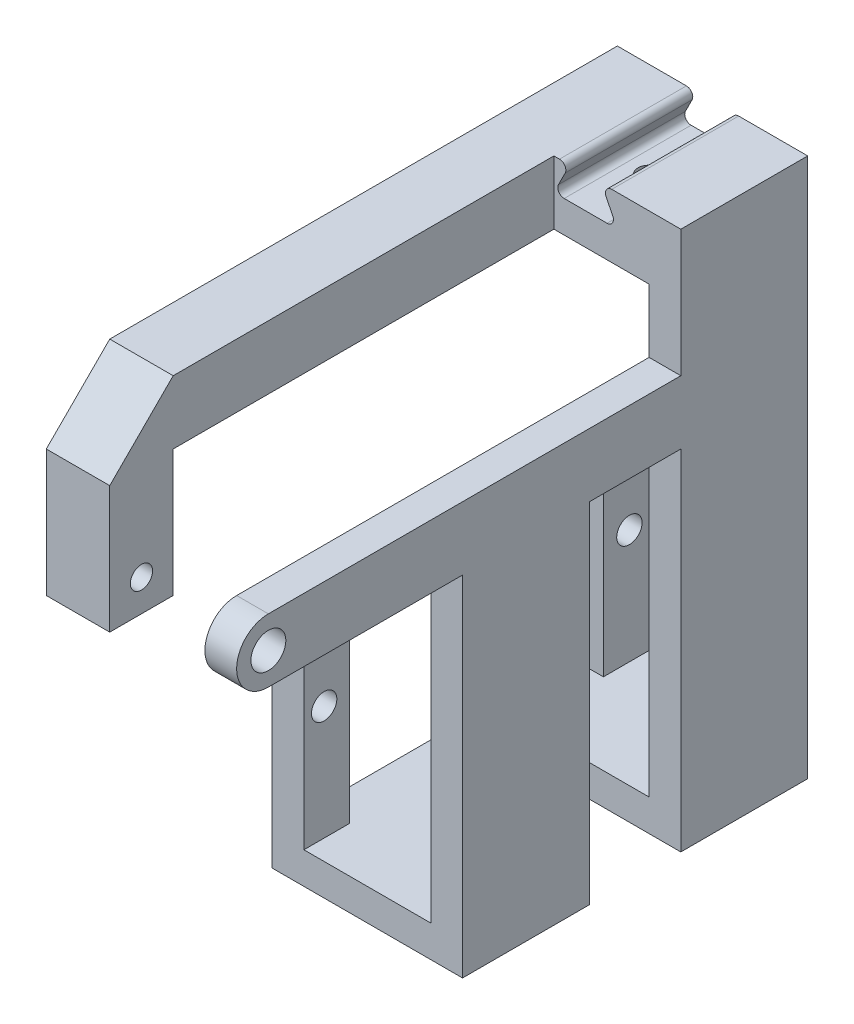
SolidWorks part; units mm, degrees
ref_plane "Plano frontal" through (0, 0, 0) normal (0, 0, 1) x (1, 0, 0)
ref_plane "Plano superior" through (0, 0, 0) normal (0, 1, 0) x (1, 0, 0)
ref_plane "Plano direito" through (0, 0, 0) normal (1, 0, 0) x (0, 0, -1)
sketch "Esboço1" plane through (0, 0, 0) normal (0, 0, 1) x (1, 0, 0)
  line L1 (-15, 45) -> (15, 45)
  line L2 (-15, 45) -> (-15, -45)
  line L3 (-15, -45) -> (15, -45)
  line L4 (15, 45) -> (15, 35)
  line L6 (-15, 35) -> (15, 35)
  line L7 (-10, 35) -> (-10, -45)
  line L8 (-10, -35) -> (15, -35)
  line L9 (10, -35) -> (10, -2)
  line L10 (10, -2) -> (15, -2)
  line L11 (15, -2) -> (15, -35)
  line L12 (15, -35) -> (15, -45)
  line L13 (-2.5, 45) -> (-5, 40)
  line L14 (-5, 40) -> (5, 40)
  line L15 (5, 40) -> (2.5, 45)
  point P1 (-15, 0)
  point P6 (0, 45)
  point P22 (0, 40)
  dimension "D1" = 30
  dimension "D2" = 90
  dimension "D4" = 10
  dimension "D5" = 5
  dimension "D6" = 10
  dimension "D7" = 5
  dimension "D8" = 33
  dimension "D9" = 20
  dimension "D10" = 5
  dimension "D11" = 10
  dimension "D12" = 5
extrude "Ressalto-extrusão1" add sketch "Esboço1" along normal blind 80 contours L15 L14 L13 L1 L2 L6 L4 | L7 L6 L2 L3 | L12 L8 L7 L3 | L11 L10 L9 L8
sketch "Esboço2" plane through (15, 0, 0) normal (1, 0, 0) x (0, 0, -1)
  line L5 (-80, -2) -> (0, -2) construction
  line L6 (-47.2, -2) -> (-7.2, -2)
  line L7 (-47.2, -2) -> (-47.2, -35)
  line L8 (-47.2, -35) -> (-7.2, -35)
  line L9 (-7.2, -2) -> (-7.2, -35)
  line L10 (-80, -45) -> (0, -45) construction
  line L11 (0, -2) -> (0, -45) construction
  line L13 (-80, -2) -> (-54.4, -2)
  line L14 (-80, -2) -> (-80, -35)
  line L15 (-80, -35) -> (-54.4, -35)
  line L16 (-54.4, -2) -> (-54.4, -35)
  dimension "D1" = 10
  dimension "D2" = 40
  dimension "D3" = 7.2
  dimension "D4" = 7.2
extrude "Corte-extrusão1" cut sketch "Esboço2" against normal blind 19
sketch "Esboço4" plane through (10, 0, 0) normal (-1, 0, 0) x (0, 0, 1)
  circle A0 centre (3.1042, -7.0008) radius 2
  circle A1 centre (3.1042, -17.0025) radius 2
  circle A2 centre (51.2105, -17.0025) radius 2
  circle A3 centre (51.2105, -7.0008) radius 2
extrude "Corte-extrusão3" cut sketch "Esboço4" against normal blind 12
sketch "Esboço5" plane through (15, 0, 0) normal (1, 0, 0) x (0, 0, -1)
  line L0 (-90, 35) -> (-80, 45)
  line L1 (-90, 35) -> (-80, 35)
  line L2 (-90, 35) -> (-90, 15)
  line L3 (-90, 15) -> (-80, 15)
  line L4 (-80, 35) -> (-80, 15)
  line L5 (-80, 45) -> (-80, 35)
  line M5 (-80, 45) -> (-80, 35)
  dimension "D1" = 10
  dimension "D2" = 20
extrude "Ressalto-extrusão2" add sketch "Esboço5" against normal blind 10 contours L4 L1 L2 L3 | L0 L1 M5
sketch "Esboço6" plane through (15, 0, 0) normal (1, 0, 0) x (0, 0, -1)
  line L2 (-80, 35) -> (-80, 15) construction
  line L3 (-90, 15) -> (-80, 15) construction
  circle A0 centre (-85, 20) radius 1.75
  dimension "D3" = 3.5
  dimension "D1" = 5
  dimension "D2" = 5
extrude "Corte-extrusão4" cut sketch "Esboço6" against normal blind 15
sketch "Esboço7" plane through (15, 0, 0) normal (1, 0, 0) x (0, 0, -1)
  line L1 (-81.75, 21.8764) -> (-85, 23.7528)
  line L2 (-85, 23.7528) -> (-88.25, 21.8764)
  line L3 (-88.25, 21.8764) -> (-88.25, 18.1236)
  line L4 (-88.25, 18.1236) -> (-85, 16.2472)
  line L5 (-85, 16.2472) -> (-81.75, 18.1236)
  line L6 (-81.75, 18.1236) -> (-81.75, 21.8764)
  circle A0 centre (-85, 20) radius 3.25 construction
  dimension "D1" = 6.5
extrude "Corte-extrusão5" cut sketch "Esboço7" against normal blind 5
sketch "Esboço8" plane through (-15, 0, 0) normal (-1, 0, 0) x (0, 0, 1)
  line L0 (85, 15) -> (80, 15)
  line L1 (80, 15) -> (80, 25)
  line L2 (80, 35) -> (80, 15) construction
  line L3 (80, 25) -> (85, 25)
  circle A0 centre (85, 20) radius 2.75
  circle A1 centre (85, 20) radius 5
  line M3 (80, -45) -> (80, 45)
  dimension "D1" = 5.5
extrude "Ressalto-extrusão3" add sketch "Esboço8" against normal blind 5 contours A1 L3 L1 | A1 A0 | A1 L0 M3
sketch "Esboço9" plane through (0, 0, 80) normal (0, 0, 1) x (1, 0, 0)
  line L0 (-10, 15) -> (-10, -35) construction
  line L1 (-15, -45) -> (-10, -45)
  line L2 (-15, -45) -> (-15, 15)
  line L3 (-15, 15) -> (-10, 15)
  line L4 (-10, -45) -> (-10, 15)
  line L6 (-10, -45) -> (15, -45)
  line L7 (-10, -45) -> (-10, -35)
  line L8 (-10, -35) -> (15, -35)
  line L9 (15, -45) -> (15, -35)
  line L10 (-10, 15) -> (-15, 15) construction
  line L12 (-15, 25) -> (5, 25)
  line L13 (-15, 25) -> (-15, 45)
  line L14 (-15, 45) -> (5, 45)
  line L15 (5, 25) -> (5, 45)
  line M2 (-10, -35) -> (-10, 15)
  line M3 (-10, 15) -> (-15, 15)
  line M4 (-15, 15) -> (-15, -45)
  line M5 (-15, -45) -> (15, -45)
  line M6 (15, -45) -> (15, -35)
  line M7 (15, -35) -> (-10, -35)
extrude "Corte-extrusão6" cut sketch "Esboço9" against normal up to surface (25.6 mm away) contours L12 L15 L14 L13 | L4 M5 M2 M3 M4 | L4 M5 M6 M7 up to face at (12.5, -18.5, 54.4)
sketch "Esboço11" plane through (-15, 0, 0) normal (-1, 0, 0) x (0, 0, 1)
  line L0 (54.4, -45) -> (0, -45) construction
  line L1 (54.4, 45) -> (20, 45)
  line L2 (54.4, 45) -> (54.4, 25)
  line L3 (54.4, 25) -> (20, 25)
  line L4 (20, 45) -> (20, 25)
  line L5 (34.4, -45) -> (20, -45)
  line L6 (34.4, -45) -> (34.4, 15)
  line L7 (34.4, 15) -> (20, 15)
  line L8 (20, -45) -> (20, 15)
  line L9 (0, 45) -> (0, -45) construction
  line L10 (54.4, 15) -> (54.4, -45) construction
  line L11 (54.4, 25) -> (85, 25) construction
  line L13 (85, 15) -> (54.4, 15) construction
  dimension "D1" = 20
  dimension "D2" = 20
  dimension "D3" = 20
extrude "Corte-extrusão7" cut sketch "Esboço11" against normal up to surface (20 mm away)
sketch "Esboço12" plane through (0, 40, 0) normal (0, 1, 0) x (1, 0, 0)
  line L0 (15, -80) -> (15, 0) construction
  line L1 (5, -20) -> (-5, -20) construction
  circle A0 centre (0, -10) radius 1.75
  dimension "D1" = 3.5
  dimension "D2" = 15
  dimension "D3" = 10
extrude "Corte-extrusão8" cut sketch "Esboço12" against normal blind 25
sketch "Esboço13" plane through (0, 35, 0) normal (0, -1, 0) x (1, 0, 0)
  line L1 (0, 6.2472) -> (3.25, 8.1236)
  line L2 (3.25, 8.1236) -> (3.25, 11.8764)
  line L3 (3.25, 11.8764) -> (0, 13.7528)
  line L4 (0, 13.7528) -> (-3.25, 11.8764)
  line L5 (-3.25, 11.8764) -> (-3.25, 8.1236)
  line L6 (-3.25, 8.1236) -> (0, 6.2472)
  circle A0 centre (0, 10) radius 3.25 construction
  dimension "D1" = 6.5
extrude "Corte-extrusão9" cut sketch "Esboço13" against normal blind 2.5
fillet "Filete1" radius 1 2 edges at (-2.5, 45, 10) (2.5, 45, 10)
fillet "Filete2" radius 1 2 edges at (-5, 40, 10) (5, 40, 10)
mirror "Espelhar1" about plane through (15, 0, 80) normal (1, 0, 0) of bodies 112
sketch "Esboço14" plane through (0, 0, 54.4) normal (0, 0, 1) x (1, 0, 0)
  line L0 (-15, -45) -> (45, -45) construction
  line L1 (15, -45) -> (-15, -45)
  line L2 (15, -45) -> (15, 45)
  line L3 (15, 45) -> (-15, 45)
  line L4 (-15, -45) -> (-15, 45)
extrude "Corte-extrusão10" cut sketch "Esboço14" against normal blind 84 and the other way blind 74
sketch "Esboço15" plane through (0, 0, 54.4) normal (0, 0, 1) x (1, 0, 0)
  line L0 (45, 15) -> (45, -45) construction
  line L1 (15, -45) -> (45, -45)
  line L2 (15, -45) -> (15, -40)
  line L3 (15, -40) -> (45, -40)
  line L4 (45, -45) -> (45, -40)
  dimension "D1" = 5
extrude "Corte-extrusão11" cut sketch "Esboço15" against normal blind 120
sketch "Esboço16" plane through (40, 0, 0) normal (-1, 0, 0) x (0, 0, 1)
  line L0 (20, 25) -> (85, 25) construction
  line L1 (34.4, 15) -> (34.4, -35) construction
  line L2 (20, 15) -> (34.4, 15) construction
  circle A0 centre (29.4, 20) radius 1
  circle A1 centre (44.4, 10) radius 1
  dimension "D1" = 2
  dimension "D6" = 2
  dimension "D2" = 5
  dimension "D3" = 5
  dimension "D4" = 10
  dimension "D5" = 5
extrude "Corte-extrusão12" cut sketch "Esboço16" against normal blind 2
